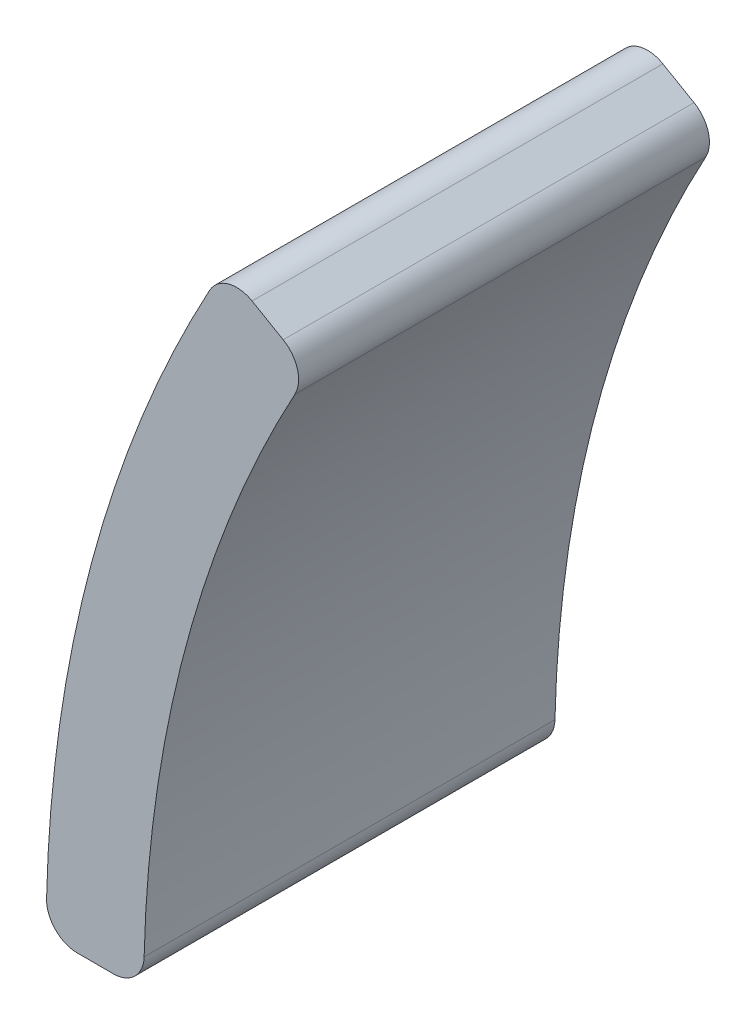
SolidWorks part; units mm, degrees
ref_plane "前视基准面" through (0, 0, 0) normal (0, 0, 1) x (1, 0, 0)
ref_plane "上视基准面" through (0, 0, 0) normal (0, 1, 0) x (1, 0, 0)
ref_plane "右视基准面" through (0, 0, 0) normal (1, 0, 0) x (0, 0, -1)
other "Configuration Table"
sketch "草图1" plane through (0, 0, 0) normal (0, 0, 1) x (1, 0, 0)
  line L0 (-161.291, 0) -> (169.8956, 0)
  line L1 (0, 0) -> (-158.8992, 91.7405)
  circle A0 centre (0, 0) radius 120.5
  circle A1 centre (0, 0) radius 130
  dimension "D1" = 241
  dimension "D2" = 260
  dimension "D3" = 30
extrude "凸台-拉伸1" add sketch "草图1" along normal blind 40 contours L1 A1 L0 A0
fillet "圆角1" radius 3 4 edges at (-130, 0, 20) (-120.5, 0, 20) (-112.5833, 65, 20) (-104.3561, 60.25, 20)
sketch "草图2" plane through (0, 0, 0) normal (0, 0, -1) x (-1, 0, 0)
  line L0 (0, 0) -> (152.9385, 0) construction
  line L1 (125.0224, 10.938) -> (0, 0) construction
  line L2 (113.7416, 53.0386) -> (0, 0) construction
  circle A0 centre (0, 0) radius 125.5 construction
  circle A1 centre (125.0224, 10.938) radius 2
  circle A2 centre (113.7416, 53.0386) radius 2
  dimension "D1" = 251
  dimension "D2" = 4
  dimension "D3" = 4
  dimension "D4" = 5
  dimension "D5" = 20
extrude "切除-拉伸1" cut sketch "草图2" against normal blind 10
